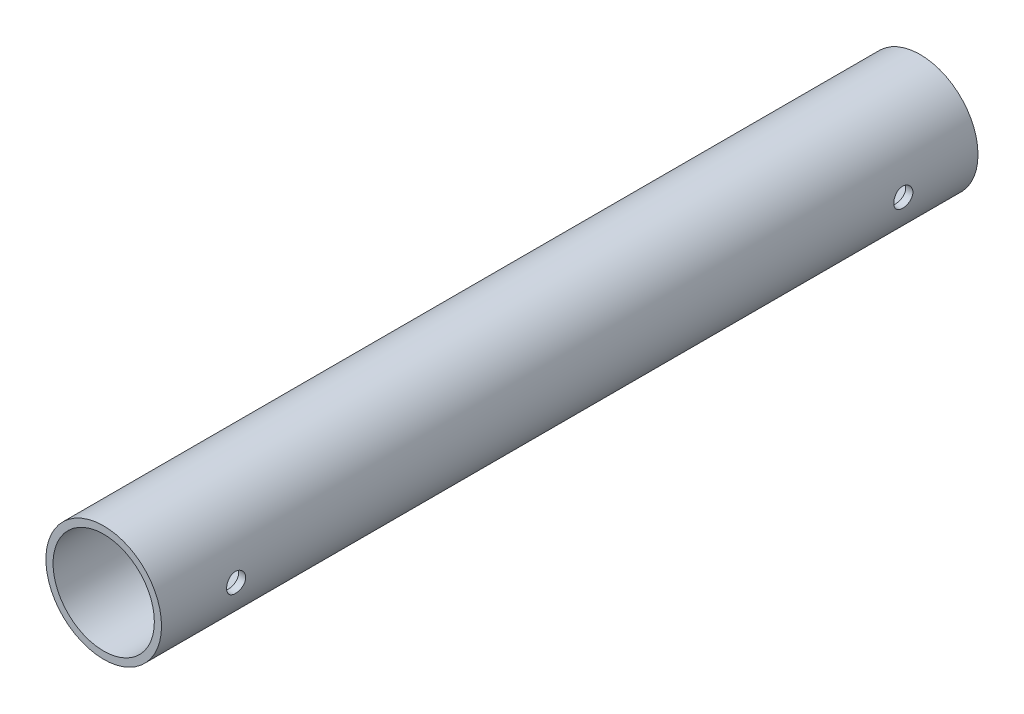
SolidWorks part; units mm, degrees
ref_plane "Front Plane" through (0, 0, 0) normal (0, 0, 1) x (1, 0, 0)
ref_plane "Top Plane" through (0, 0, 0) normal (0, 1, 0) x (1, 0, 0)
ref_plane "Right Plane" through (0, 0, 0) normal (1, 0, 0) x (0, 0, -1)
sketch "Sketch1" plane through (0, 0, 0) normal (0, 0, 1) x (1, 0, 0)
  circle A0 centre (0, 0) radius 10.6
  circle A1 centre (0, 0) radius 12.1
  dimension "D1" = 24.2
  dimension "D2" = 1.5
extrude "Boss-Extrude1" add sketch "Sketch1" along normal blind 85.445
sketch "Sketch2" plane through (0, 0, 0) normal (1, 0, 0) x (0, 0, -1)
  line L0 (-85.445, 12.1) -> (-85.445, -12.1) construction
  circle A0 centre (-69.82, 0) radius 2
  dimension "D1" = 4
  dimension "D2" = 15.625
extrude "Cut-Extrude1" cut sketch "Sketch2" against normal through all both and the other way through all
mirror "Mirror1" about plane through (0, 0, 0) normal (0, 0, 1) of "Boss-Extrude1", "Cut-Extrude1"
